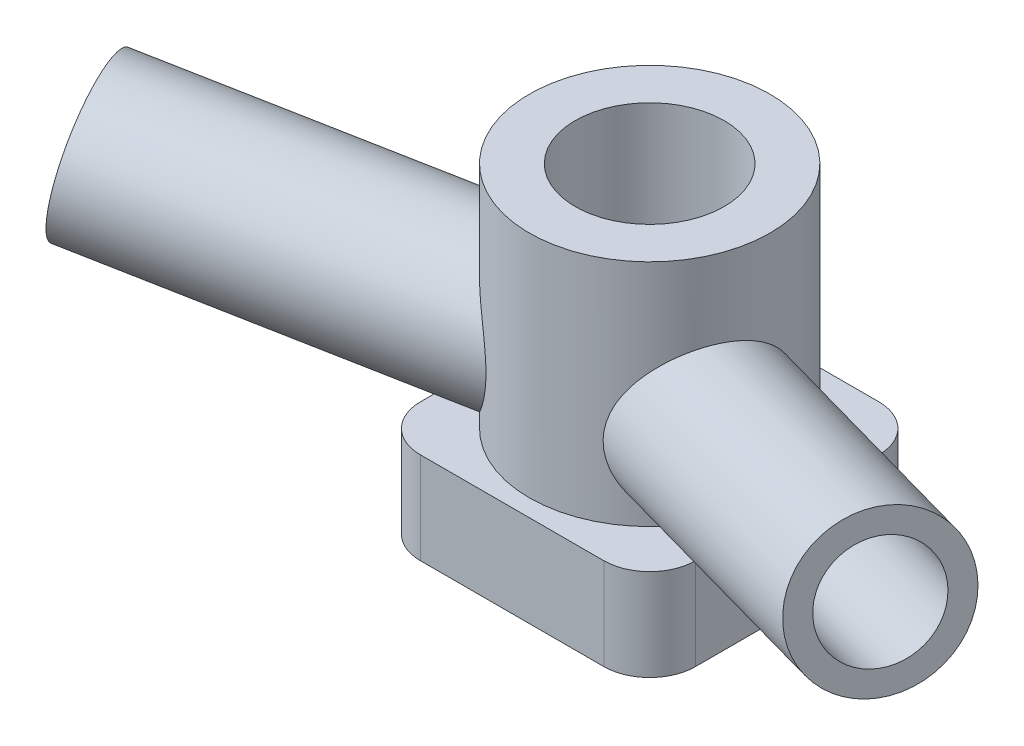
SolidWorks part; units mm, degrees
ref_plane "Plan de face" through (0, 0, 0) normal (0, 0, 1) x (1, 0, 0)
ref_plane "Plan de dessus" through (0, 0, 0) normal (0, 1, 0) x (1, 0, 0)
ref_plane "Plan de droite" through (0, 0, 0) normal (1, 0, 0) x (0, 0, -1)
sketch "Esquisse1" plane through (0, 0, 0) normal (0, 1, 0) x (1, 0, 0)
  line L1 (0, 6) -> (6, 6)
  line L2 (0, 6) -> (0, -6)
  line L3 (0, -6) -> (6, -6)
  line L4 (6, 6) -> (6, -6)
  dimension "D1" = 6
  dimension "D2" = 12
  dimension "D3" = 0
  dimension "D4" = 6
extrude "Boss.-Extru.1" add sketch "Esquisse1" along normal blind 4 contours L1 L4 L3 L2
sketch "Esquisse2" plane through (0, 4, 0) normal (0, 1, 0) x (1, 0, 0)
  line L0 (0, 6) -> (0, -6) construction
  arc A0 (0, 3.25) -> (0, -3.25) centre (0, 0) cw
  dimension "D1" = 3.25
  dimension "D2" = 0
extrude "Extru.-Mince1" add sketch "Esquisse2" along normal blind 10 thin thin type one direction reverse wall 2
sketch "Esquisse5" plane through (0, 4, 0) normal (0, 1, 0) x (1, 0, 0)
  line L0 (6, 6) -> (1, -6)
  line L1 (0, -6) -> (6, -6) construction
  line L2 (0, -5.25) -> (0, -6) construction
  dimension "D1" = 1
ref_plane "Plan2" through (3.5237, 0.6731, 1.4682) normal (-0.9091, -0.1736, -0.3788) x (-0.3846, 0, 0.9231)
sketch "Esquisse4" plane through (3.5237, 0.6731, 1.4682) normal (-0.9091, -0.1736, -0.3788) x (-0.3846, 0, 0.9231)
  circle A0 centre (0, 6.2723) radius 2.25
  circle A1 centre (0, 6.2723) radius 3.25
  dimension "D1" = 4.5
  dimension "D2" = 6.5
extrude "Boss.-Extru.3" add sketch "Esquisse4" against normal blind 15 from offset 1.2 contours A1 | A0 offset against normal yes
mirror "Symétrie1" about plane through (0, 4, -6) normal (1, 0, 0) of bodies 104
fillet "Congé1" radius 2 4 edges at (-6, 2, 6) (-6, 2, -6) (6, 2, -6) (6, 2, 6)
